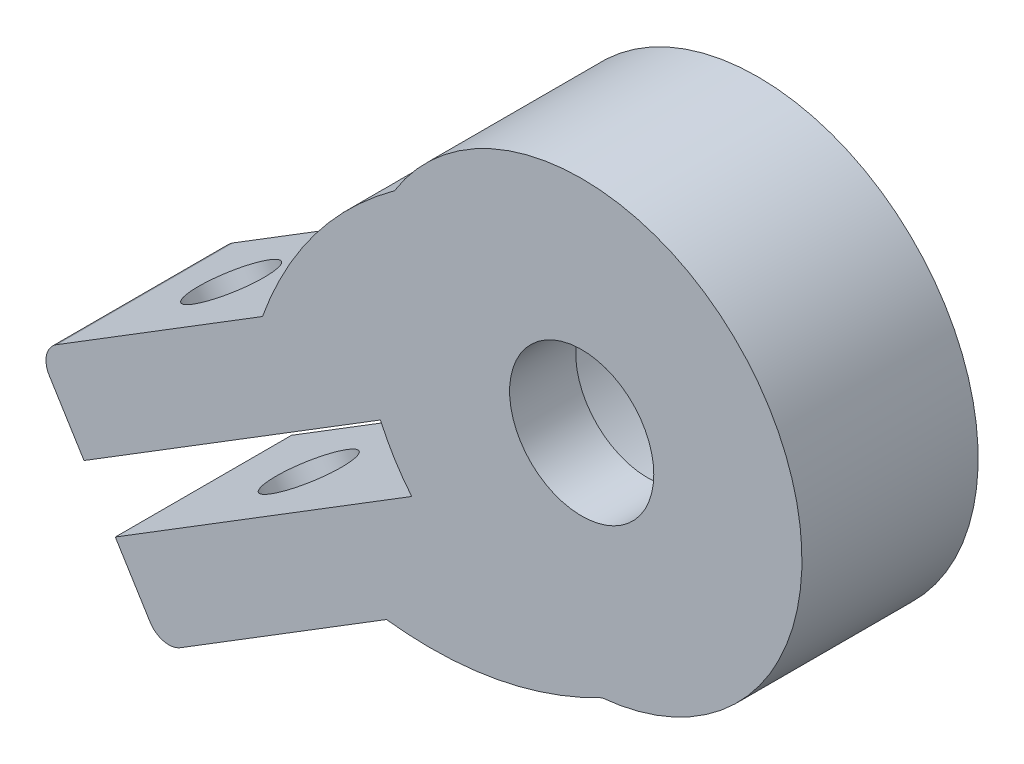
SolidWorks part; units mm, degrees
ref_plane "Front Plane" through (0, 0, 0) normal (0, 0, 1) x (1, 0, 0)
ref_plane "Top Plane" through (0, 0, 0) normal (0, 1, 0) x (1, 0, 0)
ref_plane "Right Plane" through (0, 0, 0) normal (1, 0, 0) x (0, 0, -1)
sketch "Sketch1" plane through (0, 0, 0) normal (0, 0, 1) x (1, 0, 0)
  circle A1 centre (0, 0) radius 6.925
  circle A2 centre (0, 0) radius 10
  dimension "D1" = 20
  dimension "D2" = 13.85
extrude "Boss-Extrude1" add sketch "Sketch1" against normal blind 5
sketch "Sketch2" plane through (0, 0, 0) normal (0, 0, 1) x (1, 0, 0)
  circle A1 centre (0, 0) radius 10
  circle A2 centre (0, 0) radius 10
  dimension "D1" = 0
sketch "Sketch3" plane through (0, 0, 0) normal (0, 0, 1) x (1, 0, 0)
  circle A0 centre (0, 0) radius 3.2729
  circle A1 centre (0, 0) radius 10
extrude "Boss-Extrude2" add sketch "Sketch3" along normal blind 3
sketch "Sketch4" plane through (0, 0, -5) normal (0, 0, -1) x (-1, 0, 0)
  line L0 (8.8644, -11.7732) -> (18.2196, -17.5594)
  line L1 (24.1725, -9.8359) -> (22.5944, -12.3873)
  line L2 (9.137, -4.0639) -> (22.5944, -12.3873)
  line L3 (7.7168, -6.3602) -> (21.1742, -14.6836)
  line L4 (25.5552, -15.8059) -> (-0.7636, 0.4723) construction
  line L5 (21.1742, -14.6836) -> (19.5961, -17.235)
  line L6 (14.4928, -2.6732) -> (23.848, -8.4594)
  arc A0 (-0.9203, -9.9576) -> (8.4983, 5.2705) centre (0, 0) ccw
  arc A1 (18.2196, -17.5594) -> (19.5961, -17.235) centre (18.7456, -16.709) ccw
  arc A2 (23.848, -8.4594) -> (24.1725, -9.8359) centre (23.322, -9.3098) cw
  spline S0 degree 2 poles (8.4983, 5.2705) (12.76, 2.1534) (14.4928, -2.6732) knots 0 0 0 1 1 1
  spline S1 degree 2 poles (-0.9203, -9.9576) (3.772, -12.3785) (8.8644, -11.7732) knots 0 0 0 1 1 1
  point P19 (19.0701, -18.0855)
  point P22 (24.6985, -8.9854)
  circle M6 centre (0, 0) radius 10
  dimension "D1" = 4
  dimension "D3" = 1
  dimension "D2" = 12
extrude "Boss-Extrude3" add sketch "Sketch4" against normal up to surface (8 mm away) contours S0 L2 L1 A2 L6 M6 | S1 L0 A1 L5 L3 M6 up to face at (10, 0, 3)
sketch "Sketch5" plane through (2.8142, -4.55, 0) normal (0.526, -0.8505, 0) x (0.8505, 0.526, 0)
  circle A0 centre (-10.422, -1) radius 1.75
  circle A1 centre (-20.1088, -1) radius 1.75
  dimension "D1" = 3.5
  dimension "D2" = 3.5
extrude "Cut-Extrude1" cut sketch "Sketch5" against normal through all and the other way through all
sketch "Sketch6" plane through (2.8142, -4.55, 0) normal (0.526, -0.8505, 0) x (0.8505, 0.526, 0)
  circle A0 centre (-10.422, -1) radius 3.5
  dimension "D1" = 7
extrude "Cut-Extrude2" cut sketch "Sketch6" along normal through all
ref_plane "Plane1" through (0, 0, 0) normal (0.526, -0.8505, 0) x (-0.8505, -0.526, 0)
mirror "Mirror1" about plane through (0, 0, 0) normal (0.526, -0.8505, 0) of "Cut-Extrude2"
